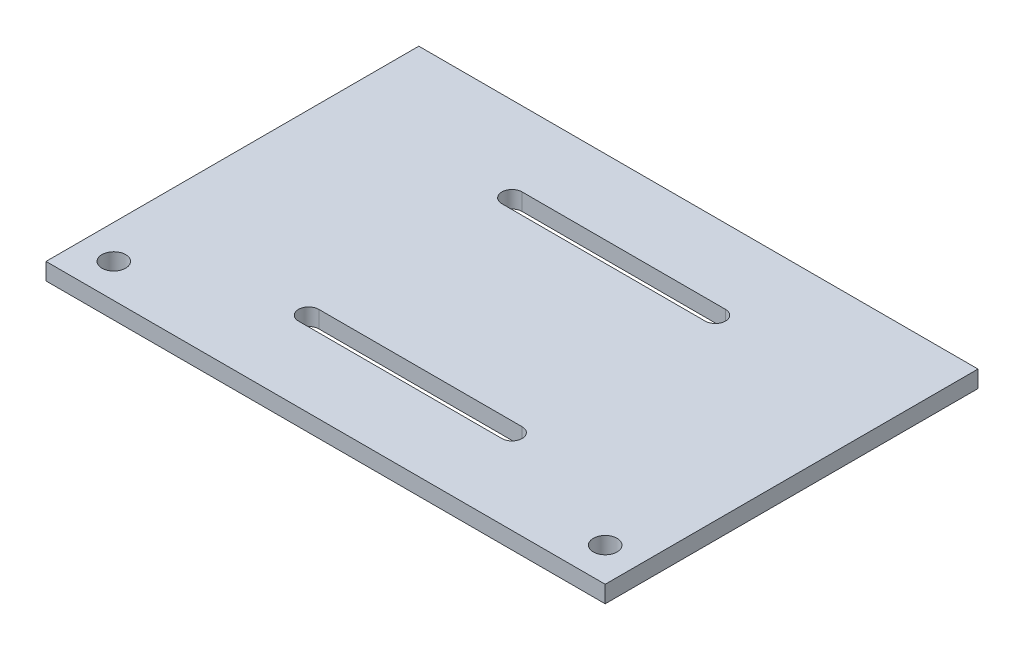
SolidWorks part; units mm, degrees
ref_plane "Front Plane" through (0, 0, 0) normal (0, 0, 1) x (1, 0, 0)
ref_plane "Top Plane" through (0, 0, 0) normal (0, 1, 0) x (1, 0, 0)
ref_plane "Right Plane" through (0, 0, 0) normal (1, 0, 0) x (0, 0, -1)
sketch "Sketch1" plane through (0, 0, 0) normal (0, 1, 0) x (1, 0, 0)
  line L2 (-82.5, 55) -> (-82.5, -55)
  line L3 (-82.5, -55) -> (82.5, -55)
  line L4 (82.5, 55) -> (82.5, -55)
  line L5 (-82.5, 55) -> (82.5, -55) construction
  line L6 (-82.5, -55) -> (82.5, 55) construction
  line L11 (82.5, 55) -> (-82.5, 55)
  line L12 (30, -30) -> (-30, -30) construction
  line L13 (30, -33) -> (-30, -33)
  line L14 (30, -27) -> (-30, -27)
  line L15 (30, 30) -> (-30, 30) construction
  line L16 (30, 27) -> (-30, 27)
  line L17 (30, 33) -> (-30, 33)
  circle A0 centre (72.5, -45) radius 3.5
  circle A1 centre (-72.5, -45) radius 3.5
  arc A14 (30, -33) -> (30, -27) centre (30, -30) ccw
  arc A15 (-30, -27) -> (-30, -33) centre (-30, -30) ccw
  arc A16 (30, 27) -> (30, 33) centre (30, 30) ccw
  arc A17 (-30, 33) -> (-30, 27) centre (-30, 30) ccw
  point P0 (0, 0)
  point P10 (0, 0)
  point P13 (0, -30)
  point P18 (0, 30)
  point P25 (0, 0)
  dimension "D3" = 7
  dimension "D10" = 3
  dimension "D1" = 110
  dimension "D2" = 165
  dimension "D4" = 10
  dimension "D5" = 10
  dimension "D6" = 10
  dimension "D7" = 60
  dimension "D8" = 30
  dimension "D9" = 60
extrude "Boss-Extrude1" add sketch "Sketch1" along normal blind 5
